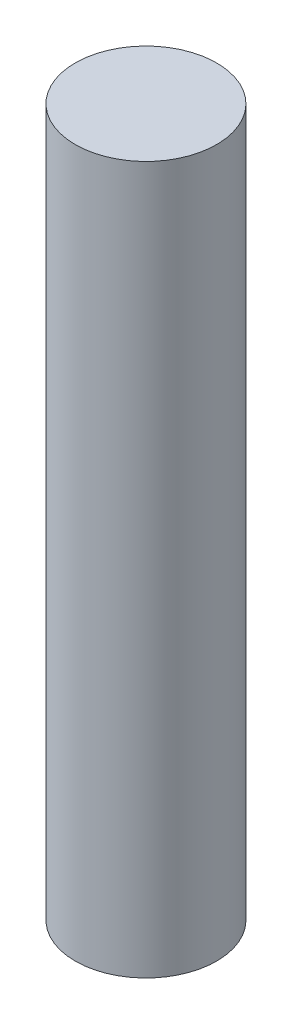
SolidWorks part; units mm, degrees
ref_plane "Ön Düzlem" through (0, 0, 0) normal (0, 0, 1) x (1, 0, 0)
ref_plane "Üst Düzlem" through (0, 0, 0) normal (0, 1, 0) x (1, 0, 0)
ref_plane "Sağ Düzlem" through (0, 0, 0) normal (1, 0, 0) x (0, 0, -1)
sketch "Çizim2" plane through (0, 0, 0) normal (0, 1, 0) x (1, 0, 0)
  circle A0 centre (0, 0) radius 1
  dimension "D1" = 2
extrude "Yükseklik-Ekstrüzyon1" add sketch "Çizim2" along normal blind 10
